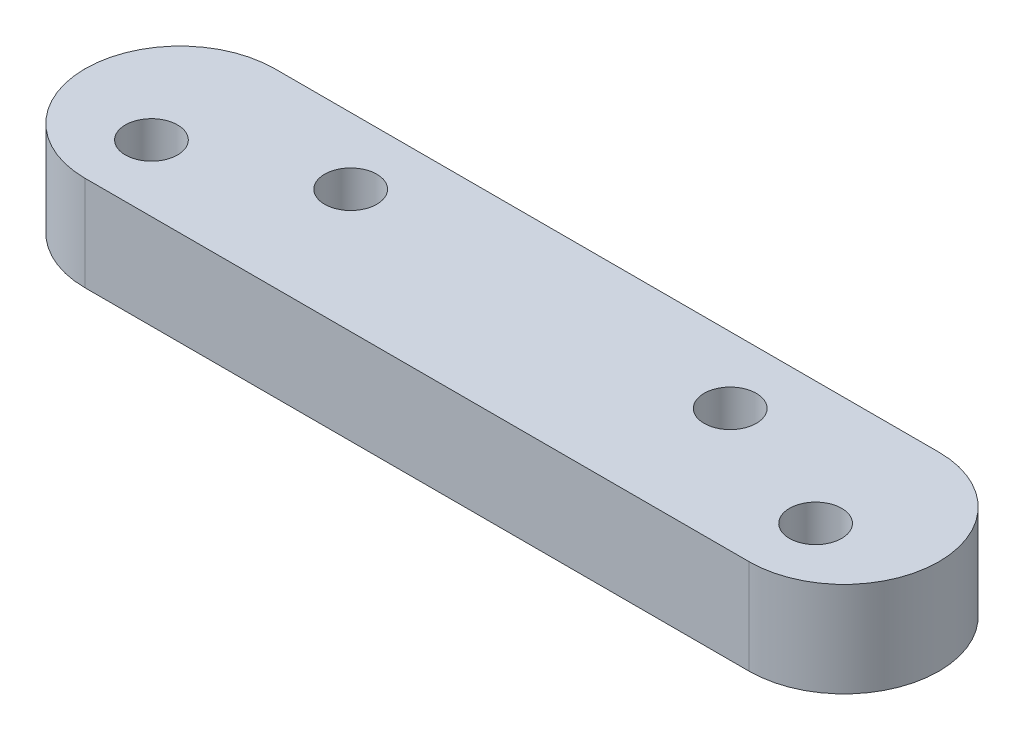
SolidWorks part; units mm, degrees
ref_plane "Front Plane" through (0, 0, 0) normal (0, 0, 1) x (1, 0, 0)
ref_plane "Top Plane" through (0, 0, 0) normal (0, 1, 0) x (1, 0, 0)
ref_plane "Right Plane" through (0, 0, 0) normal (1, 0, 0) x (0, 0, -1)
sketch "Sketch2" plane through (0, 0, 0) normal (0, 1, 0) x (1, 0, 0)
  line L0 (0, 0) -> (0, 3.8289) construction
  line L1 (-17.5, 1.5) -> (17.5, 1.5) construction
  line L4 (-17.5, 6.5) -> (17.5, 6.5)
  line L5 (-17.5, -3.5) -> (17.5, -3.5)
  circle A0 centre (10, 3) radius 1.375
  circle A1 centre (-10, 3) radius 1.375
  circle A2 centre (-17.5, 0) radius 1.375
  circle A3 centre (17.5, 0) radius 1.375
  arc A6 (-17.5, 6.5) -> (-17.5, -3.5) centre (-17.5, 1.5) ccw
  arc A7 (17.5, -3.5) -> (17.5, 6.5) centre (17.5, 1.5) ccw
  point P6 (0, 1.5)
  point P18 (10, 4.3228)
  point P19 (0, 0)
  point P20 (0, 0)
  point P21 (20.1157, 2.5)
  point P22 (0, 0)
  dimension "D1" = 2.75
  dimension "D3" = 35
  dimension "D4" = 2.75
  dimension "D6" = 5
  dimension "D2" = 20
  dimension "D5" = 1.5
  dimension "D7" = 3
  dimension "D8" = 35
extrude "Boss-Extrude1" add sketch "Sketch2" along normal blind 5
